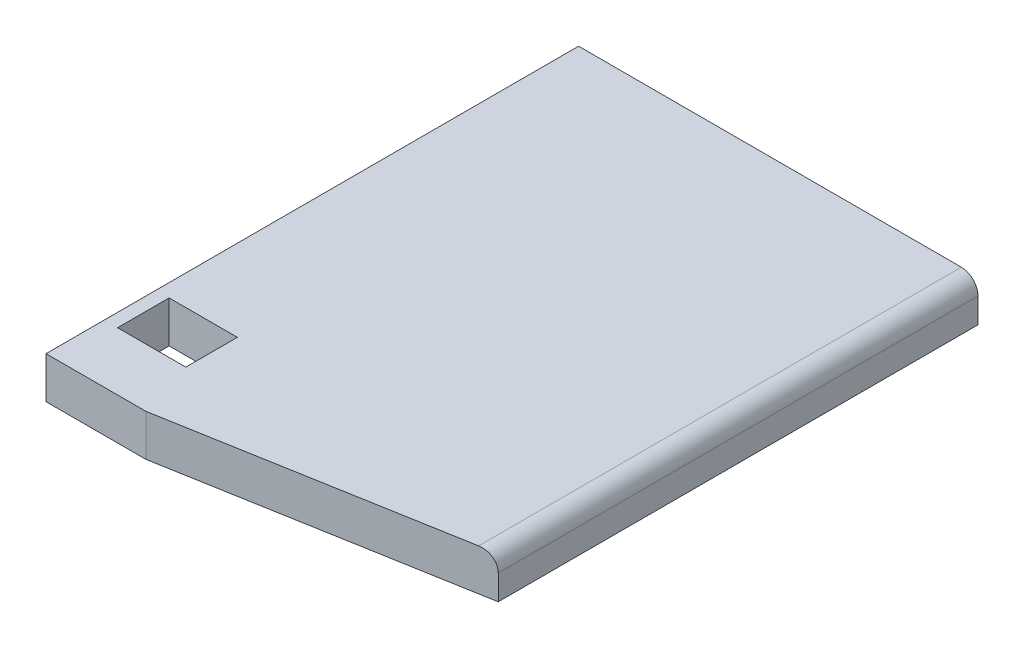
SolidWorks part; units mm, degrees
ref_plane "前视基准面" through (0, 0, 0) normal (1, 0, 0) x (0, 1, 0)
ref_plane "上视基准面" through (0, 0, 0) normal (0, 0, 1) x (0, 1, 0)
ref_plane "右视基准面" through (0, 0, 0) normal (0, 1, 0) x (-1, 0, 0)
other "Configuration Table"
sketch "草图3" plane through (0, 0, 0) normal (0, 0, 1) x (0, 1, 0)
  line L1 (0, 0) -> (2.5, 0)
  line L2 (0, 0) -> (0, -24)
  line L3 (0, -24) -> (2.5, -24)
  line L4 (2.5, 0) -> (2.5, -24)
  line L5 (0, 0) -> (2.5, -24) construction
  line L6 (0, -24) -> (2.5, 0) construction
  point P4 (1.25, -12)
  dimension "D1" = 2.5
  dimension "D2" = 24
extrude "凸台-拉伸1" add sketch "草图3" along normal blind 33
fillet "圆角1" radius 1 1 edges at (24, 2.5, 16.5)
sketch "草图4" plane through (0, 0, 0) normal (0, -1, 0) x (1, 0, 0)
  line L0 (3, 33) -> (3, 0) construction
  line L1 (0, 33) -> (24, 33) construction
  line L2 (0, 0) -> (24, 0) construction
  line L3 (0, 33) -> (0, 0) construction
  line L4 (3, 33) -> (24, 31.1627)
  line L5 (24, 33) -> (24, 0) construction
  line L6 (24, 31.1627) -> (24, 33)
  line L7 (24, 33) -> (3, 33)
  dimension "D1" = 3
  dimension "D2" = 5
extrude "切除-拉伸1" cut sketch "草图4" against normal through all
sketch "草图5" plane through (0, 0, 0) normal (-1, 0, 0) x (0, -1, 0)
  line L0 (-2.5, 33) -> (-2.5, 0) construction
  line L1 (-2.5, 28.5) -> (0, 28.5)
  line L2 (-2.5, 28.5) -> (-2.5, 25.4)
  line L3 (-2.5, 25.4) -> (0, 25.4)
  line L4 (0, 28.5) -> (0, 25.4)
  line L5 (-2.5, 28.5) -> (0, 25.4) construction
  line L6 (-2.5, 25.4) -> (0, 28.5) construction
  line L7 (0, 33) -> (0, 0) construction
  line L8 (-2.5, 33) -> (0, 33) construction
  point P4 (-1.25, 26.95)
  dimension "D1" = 4.5
  dimension "D2" = 3.1
extrude "切除-拉伸2" cut sketch "草图5" against normal blind 4.9
sketch "草图6" plane through (0, 0, 33) normal (0, 0, 1) x (1, 0, 0)
  line L1 (24, 0) -> (0, 0)
  line L2 (24, 0) -> (24, 2.5)
  line L3 (24, 2.5) -> (0, 2.5)
  line L4 (0, 0) -> (0, 2.5)
  line L5 (24, 0) -> (0, 2.5) construction
  line L6 (24, 2.5) -> (0, 0) construction
  point P4 (12, 1.25)
extrude "切除-拉伸3" cut sketch "草图6" against normal blind 1
sketch "草图7" plane through (0, 0, 0) normal (0, -1, 0) x (1, 0, 0)
  line L0 (24, 31.1627) -> (24, 0) construction
  line L1 (0, 32) -> (14.4301, 32) construction
  line L2 (14.4301, 32) -> (24, 31.1627) construction
  line L3 (24, 31.1627) -> (24, 28.8261)
  line L4 (6, 32) -> (14.4301, 32)
  line L5 (14.4301, 32) -> (24, 31.1627)
  line L6 (6, 32) -> (24, 28.8261)
  dimension "D1" = 6
  dimension "D2" = 10
extrude "切除-拉伸4" cut sketch "草图7" against normal through all
sketch "草图8" plane through (0, 2.5, 0) normal (0, 1, 0) x (-1, 0, 0)
  line L0 (-4.9, 25.4) -> (0, 25.4) construction
  line L1 (0, 28.5) -> (-0.8, 28.5)
  line L2 (0, 28.5) -> (0, 25.4)
  line L3 (0, 25.4) -> (-0.8, 25.4)
  line L4 (-0.8, 28.5) -> (-0.8, 25.4)
  line L5 (0, 28.5) -> (-0.8, 25.4) construction
  line L6 (0, 25.4) -> (-0.8, 28.5) construction
  line L7 (-4.9, 28.5) -> (-4.9, 25.4) construction
  point P4 (-0.4, 26.95)
  dimension "D1" = 4.1
  dimension "D2" = 0.8
extrude "凸台-拉伸2" add sketch "草图8" against normal up to surface (2.5 mm away) up to face at (7.0889, 0, 22.2918)
